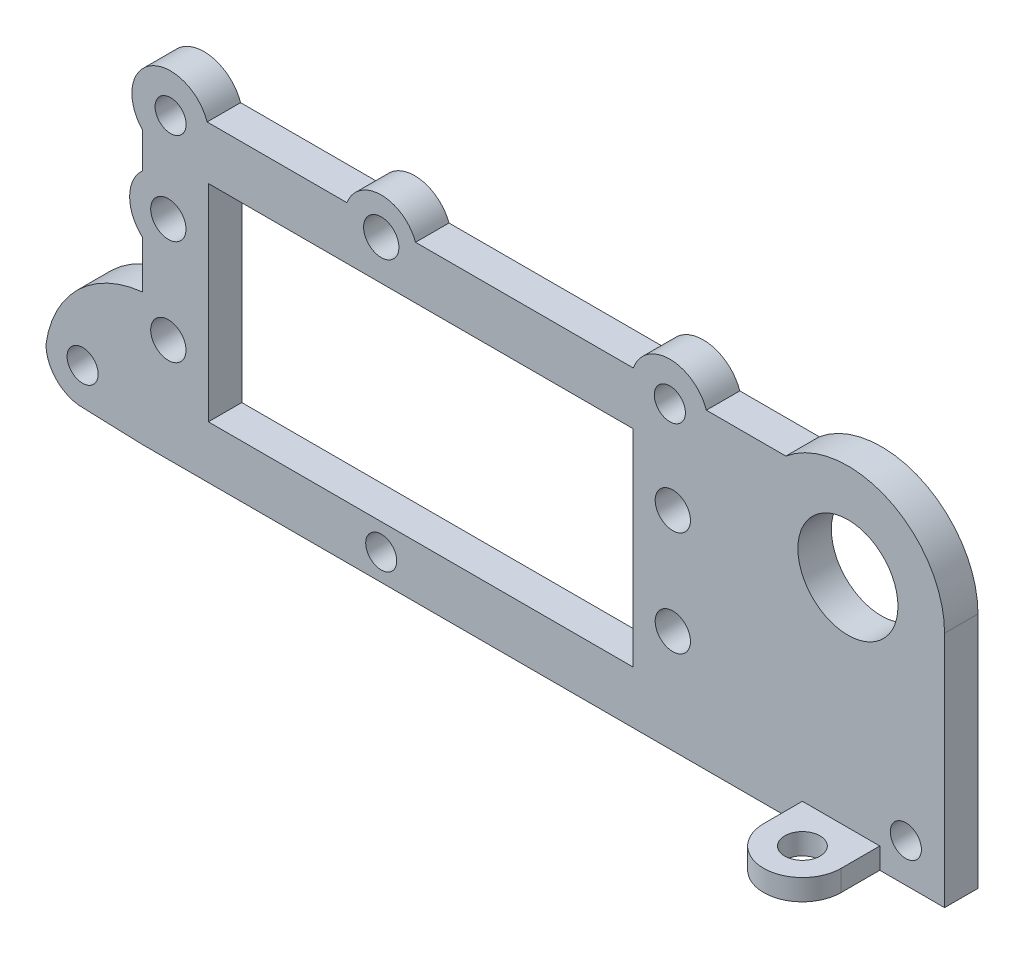
SolidWorks part; units mm, degrees
ref_plane "Front Plane" through (0, 0, 0) normal (0, 0, 1) x (1, 0, 0)
ref_plane "Top Plane" through (0, 0, 0) normal (0, 1, 0) x (1, 0, 0)
ref_plane "Right Plane" through (0, 0, 0) normal (1, 0, 0) x (0, 0, -1)
sketch "Sketch1" plane through (0, 0, 0) normal (0, 0, 1) x (1, 0, 0)
  line L1 (-26.416, -9.8) -> (26.416, -9.8)
  line L2 (-26.416, -9.8) -> (-26.416, 9.8)
  line L3 (-26.416, 9.8) -> (26.416, 9.8)
  line L4 (26.416, -9.8) -> (26.416, 9.8)
  line L5 (-26.416, -9.8) -> (26.416, 9.8) construction
  line L6 (-26.416, 9.8) -> (26.416, -9.8) construction
  line L7 (-20.15, -9.8) -> (20.15, -9.8)
  line L8 (-20.15, -9.8) -> (-20.15, 9.8)
  line L9 (-20.15, 9.8) -> (20.15, 9.8)
  line L10 (20.15, -9.8) -> (20.15, 9.8)
  line L11 (-20.15, -9.8) -> (20.15, 9.8) construction
  line L12 (-20.15, 9.8) -> (20.15, -9.8) construction
  line L13 (-26.416, 9.8) -> (26.416, 9.8)
  line L14 (-26.416, 9.8) -> (-26.416, 14.8)
  line L15 (-26.416, 14.8) -> (26.416, 14.8)
  line L16 (26.416, 9.8) -> (26.416, 14.8)
  line L17 (26.416, -9.8) -> (-26.416, -9.8)
  line L18 (26.416, -9.8) -> (26.416, -14.8)
  line L19 (26.416, -14.8) -> (-26.416, -14.8)
  line L20 (-26.416, -9.8) -> (-26.416, -14.8)
  circle A0 centre (-23.95, -4.974) radius 1.675
  circle A1 centre (-23.95, 4.974) radius 1.675
  circle A2 centre (23.95, 4.974) radius 1.675
  circle A3 centre (23.95, -4.974) radius 1.675
  point P0 (0, 0)
  point P14 (0, 0)
  dimension "D1" = 3.35
  dimension "D2" = 3.35
  dimension "D3" = 3.35
  dimension "D4" = 3.35
  dimension "D7" = 4.826
  dimension "D8" = 3.8
  dimension "D9" = 3.8
  dimension "D10" = 4.826
  dimension "D11" = 4.826
  dimension "D12" = 4.826
  dimension "D13" = 3.8
  dimension "D5" = 19.6
  dimension "D6" = 52.832
  dimension "D15" = 40.3
  dimension "D16" = 5
  dimension "D17" = 5
  dimension "3.9" = 3.8
extrude "Boss-Extrude2" add sketch "Sketch1" along normal blind 3.175 contours L1 L8 L3 L2 A1 A0 | L1 L20 L19 L18 | L3 L16 L15 L14 | L10 L1 L4 L3 A3 A2
sketch "Sketch3" plane through (0, 0, 3.175) normal (0, 0, 1) x (1, 0, 0)
  line L0 (26.416, -14.8) -> (56.416, -14.8)
  line L6 (26.416, 14.8) -> (56.416, 14.8)
  line L7 (26.416, 14.8) -> (26.416, -14.906)
  line L8 (26.416, -14.906) -> (56.416, -14.906)
  line L9 (56.416, 14.8) -> (56.416, -14.906)
  line M3 (26.416, -14.8) -> (26.416, 14.8)
  dimension "D2" = 30
extrude "Boss-Extrude3" add sketch "Sketch3" against normal up to surface (3.175 mm away) contours L9 L6 L0 M3 up to face at (0, 0, 0)
sketch "Sketch4" plane through (0, 0, 0) normal (0, 0, -1) x (-1, 0, 0)
  line L3 (-56.416, 14.8) -> (-56.416, -14.8) construction
  line L4 (-56.416, -14.8) -> (26.416, -14.8) construction
  circle A0 centre (-40.576, 7.77) radius 4.75
  dimension "D1" = 15.84
  dimension "D2" = 22.57
  dimension "D3" = 9.5
extrude "Cut-Extrude1" cut sketch "Sketch4" against normal blind 10 contours A0
sketch "Sketch22" plane through (0, 0, 0) normal (0, 0, -1) x (-1, 0, 0)
  line L0 (-52.3294, 14.8) -> (-30.0917, 14.8)
  line L1 (26.416, 14.8) -> (-56.416, 14.8) construction
  circle A0 centre (-40.576, 7.77) radius 9.175
  dimension "D1" = 18.35
extrude "Boss-Extrude14" add sketch "Sketch22" against normal up to surface (3.175 mm away) contours L0 A0
sketch "Sketch23" plane through (0, 0, 0) normal (0, 0, -1) x (-1, 0, 0)
  line L0 (-49.751, 7.77) -> (-49.751, -14.8)
  line L1 (-56.416, -14.8) -> (26.416, -14.8) construction
  circle A0 centre (-40.576, 7.77) radius 9.175
  line M4 (-46.4717, 14.8) -> (-56.416, 14.8)
  line M5 (-56.416, 14.8) -> (-56.416, -14.8)
  line M6 (-56.416, -14.8) -> (26.416, -14.8)
extrude "Cut-Extrude8" cut sketch "Sketch23" against normal blind 10 contours A0 L0 M4 M5 M6
sketch "Sketch24" plane through (0, 0, 0) normal (0, 0, -1) x (-1, 0, 0)
  line L1 (26.416, 14.8) -> (-34.6803, 14.8) construction
  line L2 (26.416, -14.8) -> (26.416, 14.8) construction
  circle A0 centre (23.736, 13.59) radius 1.475
  dimension "D1" = 2.95
  dimension "D2" = 1.21
  dimension "D3" = 2.68
extrude "Cut-Extrude9" cut sketch "Sketch24" against normal blind 10
sketch "Sketch25" plane through (0, 0, 0) normal (0, 0, -1) x (-1, 0, 0)
  circle A0 centre (23.736, 13.59) radius 1.675
  circle A1 centre (23.95, 4.974) radius 1.675
  circle A2 centre (23.95, -4.974) radius 1.675
  circle A7 centre (23.95, -4.974) radius 3.675
  circle A8 centre (23.95, 4.974) radius 3.675
  circle A9 centre (23.736, 13.59) radius 3.675
  dimension "D1" = 2
  dimension "D2" = 2
extrude "Boss-Extrude15" add sketch "Sketch25" against normal up to surface (3.175 mm away) up to face at (5.1596, 5.6407, 3.175)
sketch "Sketch26" plane through (0, 0, 0) normal (0, 0, -1) x (-1, 0, 0)
  line L0 (-49.751, -14.8) -> (26.416, -14.8) construction
  line L2 (-49.751, 7.77) -> (-49.751, -14.8) construction
  circle A0 centre (-46.076, -11.125) radius 1.475
  circle A1 centre (-46.076, -11.125) radius 3.475
  dimension "D1" = 2.95
  dimension "D2" = 3.675
  dimension "D3" = 3.675
  dimension "D4" = 2
extrude "Cut-Extrude12" cut sketch "Sketch26" against normal up to surface (3.175 mm away) contours A0 up to face at (-4.7057, 2.7441, 3.175)
sketch "Sketch27" plane through (0, 0, 0) normal (0, 0, -1) x (-1, 0, 0)
  line L0 (18.6003, 14.8) -> (34.0912, 14.8)
  line L1 (20.2659, 14.8) -> (-34.6803, 14.8) construction
  line L2 (26.416, -11.2494) -> (26.416, 23.8755)
  line L3 (26.416, -14.8) -> (26.416, -7.6988) construction
  line L5 (-26.3458, -14.8) -> (26.3458, -14.8)
  line L6 (-26.3458, -14.8) -> (-26.3458, 14.8)
  line L7 (-26.3458, 14.8) -> (26.3458, 14.8)
  line L8 (26.3458, -14.8) -> (26.3458, 14.8)
  line L9 (-26.3458, -14.8) -> (26.3458, 14.8) construction
  line L10 (-26.3458, 14.8) -> (26.3458, -14.8) construction
  circle A0 centre (-23.6658, 13.59) radius 1.475
  point P8 (0, 0)
  dimension "D1" = 2.68
  dimension "D2" = 1.21
  dimension "D3" = 2.95
extrude "Cut-Extrude13" cut sketch "Sketch27" against normal blind 10 contours L7 A0
sketch "Sketch28" plane through (0, 0, 0) normal (0, 0, -1) x (-1, 0, 0)
  circle A0 centre (-23.6658, 13.59) radius 1.675
  circle A1 centre (-23.6658, 13.59) radius 3.675
  dimension "D1" = 2
extrude "Boss-Extrude16" add sketch "Sketch28" against normal up to surface (3.175 mm away) contours A1 | A0 up to face at (0.0228, 4.5297, 3.175)
sketch "Sketch29" plane through (0, 0, 0) normal (0, 0, -1) x (-1, 0, 0)
  line L0 (26.416, -14.8) -> (28.416, -14.8)
  line L1 (-49.751, -14.8) -> (26.416, -14.8) construction
  line L2 (32.091, -14.6) -> (26.416, -14.8)
  line L3 (26.416, -2.2492) -> (26.416, -14.8)
  circle A0 centre (32.091, -11.125) radius 1.475
  circle A1 centre (32.091, -11.125) radius 3.475
  arc A2 (35.566, -11.125) -> (26.416, -2.2492) centre (25.3024, -12.5515) ccw
  line M7 (26.416, -14.8) -> (26.416, -7.6988)
  arc M8 (26.416, -7.6988) -> (26.416, -2.2492) centre (23.95, -4.974) ccw
  dimension "D2" = 2
  dimension "D3" = 2.95
  dimension "D4" = 3.675
  dimension "D5" = 3.675
  dimension "D1" = 2
extrude "Boss-Extrude17" add sketch "Sketch29" against normal up to surface (3.175 mm away) contours A1 A2 L0 L2 M8 M7 | A1 A2 A0
sketch "Sketch31" plane through (0, 0, 0) normal (0, 0, -1) x (-1, 0, 0)
  circle A0 centre (3.736, 13.59) radius 1.475
  circle A1 centre (23.736, 13.59) radius 1.675 construction
  circle A2 centre (3.736, 13.59) radius 3.475
  line M14 (20.2659, 14.8) -> (-20.1957, 14.8)
  dimension "D1" = 2.95
  dimension "D2" = 20
  dimension "D3" = 2
extrude "Boss-Extrude19" add sketch "Sketch31" against normal up to surface (3.175 mm away) contours A2 A0 M14 up to face at (-3.2311, 3.2564, 3.175)
sketch "Sketch32" plane through (0, 0, 0) normal (0, 0, -1) x (-1, 0, 0)
  circle A0 centre (3.736, 13.59) radius 1.675
extrude "Cut-Extrude14" cut sketch "Sketch32" against normal through all
sketch "Sketch33" plane through (0, 0, 0) normal (0, 0, -1) x (-1, 0, 0)
  line L0 (20.15, -9.8) -> (-20.15, -9.8) construction
  line L1 (3.736, -9.8) -> (3.736, -14.8)
  line L2 (-49.751, -14.8) -> (26.416, -14.8) construction
  circle A0 centre (3.736, -12.3) radius 1.475
  point P8 (3.736, -12.3)
  dimension "D1" = 2.95
  dimension "D2" = 0
extrude "Cut-Extrude15" cut sketch "Sketch33" against normal through all contours L1 A0 | L1 A0
sketch "Sketch34" plane through (0, 0, 3.175) normal (0, 0, 1) x (1, 0, 0)
  circle A0 centre (-23.736, 13.59) radius 1.475
  circle A1 centre (-23.736, 13.59) radius 2.2023
  circle A2 centre (23.6658, 13.59) radius 1.475
  circle A3 centre (23.6658, 13.59) radius 2.3102
extrude "Boss-Extrude20" add sketch "Sketch34" against normal up to surface (3.175 mm away) up to face at (-5.211, -12.3, 0)
sketch "Sketch30" plane through (0, -14.8, 0) normal (0, -1, 0) x (-1, 0, 0)
  line L0 (-49.751, -3.175) -> (26.416, -3.175) construction
  line L1 (-43.601, -6.85) -> (-43.601, -3.175)
  line L2 (-43.601, -3.175) -> (-36.251, -3.175)
  line L3 (-36.251, -3.175) -> (-36.251, -6.85)
  circle A0 centre (-39.926, -6.85) radius 1.675
  circle A1 centre (-39.926, -6.85) radius 3.675
  line M3 (-49.751, -3.175) -> (26.416, -3.175)
  dimension "D1" = 3.35
  dimension "D3" = 3.675
  dimension "D4" = 4.675
  dimension "D2" = 2
extrude "Boss-Extrude18" add sketch "Sketch30" against normal blind 2 separate body contours A1 A0 | A1 L1 M3 | A1 L3 L2
